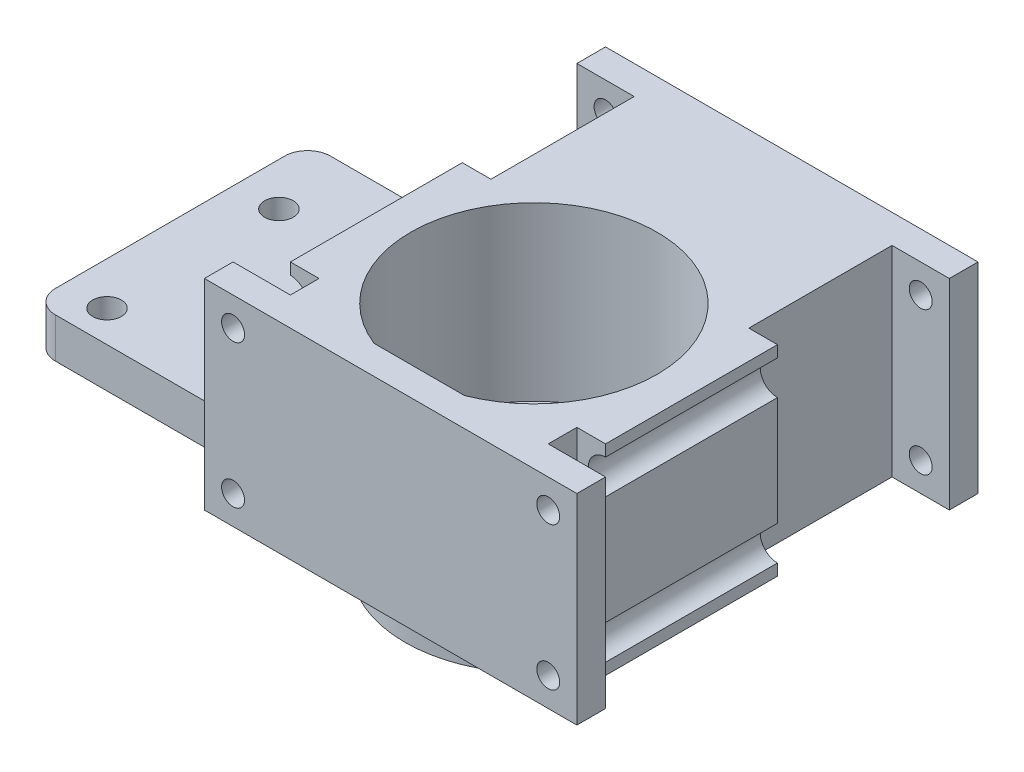
SolidWorks part; units mm, degrees
ref_plane "Front Plane" through (0, 0, 0) normal (0, 0, 1) x (1, 0, 0)
ref_plane "Top Plane" through (0, 0, 0) normal (0, 1, 0) x (1, 0, 0)
ref_plane "Right Plane" through (0, 0, 0) normal (1, 0, 0) x (0, 0, -1)
sketch "草图1" plane through (0, 0, 0) normal (0, 1, 0) x (1, 0, 0)
  line L0 (0, 0) -> (0, -10) construction
  line L1 (-22.5, -35) -> (22.5, -35)
  line L2 (-22.5, -35) -> (-22.5, 35)
  line L3 (-22.5, 35) -> (22.5, 35)
  line L4 (22.5, -35) -> (22.5, 35)
  line L5 (-22.5, -35) -> (22.5, 35) construction
  line L6 (-22.5, 35) -> (22.5, -35) construction
  circle A0 centre (0, 0) radius 21.5 construction
  circle A1 centre (0, -10) radius 21.5
  dimension "D1" = 43
  dimension "D2" = 70
  dimension "D4" = 43
  dimension "D3" = 45
  dimension "D5" = 10
extrude "凸台-拉伸1" add sketch "草图1" along normal blind 35
sketch "草图2" plane through (0, 0, 0) normal (0, -1, 0) x (1, 0, 0)
  circle A2 centre (0, 10) radius 21.5 construction
  circle A3 centre (0, 10) radius 21.5
extrude "凸台-拉伸2" add sketch "草图2" against normal blind 5
sketch "草图3" plane through (0, 0, 0) normal (0, -1, 0) x (1, 0, 0)
  line L0 (0, 27.5) -> (0, -7.5) construction
  line L1 (17.5, 10) -> (-17.5, 10) construction
  circle A0 centre (0, 10) radius 17.5 construction
  circle A1 centre (0, -7.5) radius 2
  circle A2 centre (-17.5, 10) radius 2
  circle A3 centre (0, 27.5) radius 2
  circle A4 centre (17.5, 10) radius 2
  circle A5 centre (0, 10) radius 13
  point P6 (0, 10)
  point P9 (0, 10)
  dimension "D1" = 35
  dimension "D2" = 4
  dimension "D3" = 26
  dimension "D4" = 10
extrude "切除-拉伸1" cut sketch "草图3" against normal blind 10
sketch "草图5" plane through (0, 0, -35) normal (0, 0, -1) x (-1, 0, 0)
  line L0 (-22.5, 35) -> (22.5, 35) construction
  line L1 (22.5, 0) -> (32.5, 0)
  line L2 (22.5, 0) -> (22.5, 35)
  line L3 (22.5, 35) -> (32.5, 35)
  line L4 (32.5, 0) -> (32.5, 35)
  line L5 (-22.5, 0) -> (-32.5, 0)
  line L6 (-22.5, 0) -> (-22.5, 35)
  line L7 (-22.5, 35) -> (-32.5, 35)
  line L8 (-32.5, 0) -> (-32.5, 35)
  dimension "D1" = 65
extrude "凸台-拉伸3" add sketch "草图5" against normal blind 5
sketch "草图6" plane through (0, 0, -30) normal (0, 0, 1) x (1, 0, 0)
  line L0 (0, 0) -> (0, 17.5) construction
  line L1 (-27.5, 5) -> (27.5, 5) construction
  line L2 (-27.5, 5) -> (-27.5, 30) construction
  line L3 (-27.5, 30) -> (27.5, 30) construction
  line L4 (27.5, 5) -> (27.5, 30) construction
  line L5 (-27.5, 5) -> (27.5, 30) construction
  line L6 (-27.5, 30) -> (27.5, 5) construction
  line L7 (32.5, 17.5) -> (0, 17.5) construction
  line L8 (32.5, 35) -> (32.5, 0) construction
  circle A0 centre (27.5, 30) radius 2
  circle A1 centre (27.5, 5) radius 2
  circle A2 centre (-27.5, 30) radius 2
  circle A3 centre (-27.5, 5) radius 2
  point P0 (0, 17.5)
  dimension "D3" = 4
  dimension "D1" = 55
  dimension "D2" = 25
extrude "切除-拉伸2" cut sketch "草图6" against normal blind 5
sketch "草图8" plane through (0, 0, 0) normal (0, -1, 0) x (1, 0, 0)
  circle A0 centre (0, 10) radius 22.5
  circle A1 centre (0, 10) radius 13 construction
  circle A2 centre (-17.5, 10) radius 2 construction
  circle A3 centre (0, -7.5) radius 2 construction
  circle A4 centre (0, 10) radius 13
  circle A5 centre (-17.5, 10) radius 2
  circle A6 centre (0, -7.5) radius 2
  circle A7 centre (17.5, 10) radius 2 construction
  circle A8 centre (0, 27.5) radius 2 construction
  circle A9 centre (17.5, 10) radius 2
  circle A10 centre (0, 27.5) radius 2
  dimension "D1" = 45
extrude "凸台-拉伸5" add sketch "草图8" along normal blind 5
sketch "草图9" plane through (0, -5, 0) normal (0, -1, 0) x (1, 0, 0)
  circle A0 centre (0, 27.5) radius 4
  circle A1 centre (-17.5, 10) radius 4
  circle A2 centre (17.5, 10) radius 4
  circle A3 centre (0, -7.5) radius 4
  dimension "D1" = 8
extrude "切除-拉伸3" cut sketch "草图9" against normal blind 5
sketch "草图10" plane through (0, -5, 0) normal (0, -1, 0) x (1, 0, 0)
  line L0 (0, 32.5) -> (-77, 32.5) construction
  line L1 (-77, 32.5) -> (-77, -12.5)
  line L2 (-77, -12.5) -> (0, -12.5)
  line L3 (-19.8997, 20.5) -> (-77, 20.5)
  arc A0 (22.5, 10) -> (-22.5, 10) centre (0, 10) ccw construction
  arc A1 (-22.5, 10) -> (22.5, 10) centre (0, 10) ccw construction
  circle A2 centre (0, 10) radius 22.5 construction
  arc A3 (-19.8997, 20.5) -> (0, -12.5) centre (0, 10) ccw
  circle M6 centre (0, 10) radius 22.5
  dimension "D1" = 12
  dimension "D2" = 77
extrude "凸台-拉伸6" add sketch "草图10" against normal blind 7 contours L3 L1 L2 M6
sketch "草图11" plane through (0, -5, 0) normal (0, -1, 0) x (1, 0, 0)
  line L1 (-77, -12.5) -> (-52, -12.5)
  line L2 (-77, -12.5) -> (-77, -27.5)
  line L3 (-77, -27.5) -> (-52, -27.5)
  line L4 (-52, -12.5) -> (-52, -27.5)
  dimension "D1" = 25
  dimension "D2" = 15
extrude "凸台-拉伸7" add sketch "草图11" against normal blind 7
fillet "圆角1" radius 4 4 edges at (-52, -1.5, -12.5) (-52, -1.5, -27.5) (-77, -1.5, -27.5) (-77, -1.5, 20.5)
sketch "草图12" plane through (0, -5, 0) normal (0, -1, 0) x (1, 0, 0)
  circle A0 centre (-69.5, -15) radius 2.5 construction
  circle A1 centre (-69.5, 15) radius 2.5 construction
  circle A2 centre (-69.5, -15) radius 2.5
  circle A3 centre (-69.5, 15) radius 2.5
extrude "切除-拉伸4" cut sketch "草图12" against normal blind 10
sketch "草图13" plane through (0, 0, 0) normal (0, 1, 0) x (1, 0, 0)
  line L0 (22.5, 5) -> (22.5, -25)
  line L1 (27.5, -25) -> (22.5, -25)
  line L2 (27.5, -25) -> (27.5, 5)
  line L3 (27.5, 5) -> (22.5, 5)
  line L4 (-27.5, -25) -> (-27.5, 5)
  line L5 (0, 5) -> (0, -25) construction
  line L6 (27.5, -10) -> (-27.5, -10) construction
  line L7 (22.5, -35) -> (22.5, 30) construction
  line L8 (-22.5, -25) -> (-22.5, 5)
  line L9 (-22.5, 30) -> (-22.5, -35) construction
  line L10 (-22.5, -20.5) -> (-22.5, 12.5) construction
  line L11 (-22.5, 5) -> (-27.5, 5)
  line L12 (-22.5, -25) -> (-27.5, -25)
  point P0 (0, -10)
  dimension "D1" = 55
  dimension "D2" = 30
extrude "凸台-拉伸8" add sketch "草图13" along normal blind 35
sketch "草图14" plane through (0, 0, 35) normal (0, 0, 1) x (1, 0, 0)
  line L0 (51.7919, 0) -> (-51.7919, 0) construction
  line L1 (-32.5, 35) -> (32.5, 35)
  line L2 (-32.5, 35) -> (-32.5, 0)
  line L3 (-32.5, 0) -> (32.5, 0)
  line L4 (32.5, 35) -> (32.5, 0)
  line L5 (32.5, 35) -> (32.5, 0) construction
extrude "凸台-拉伸9" add sketch "草图14" against normal blind 5
sketch "草图15" plane through (0, 0, 35) normal (0, 0, 1) x (1, 0, 0)
  line L0 (0, 35) -> (0, 0) construction
  line L1 (-32.5, 35) -> (32.5, 35) construction
  line L2 (-32.5, 17.5) -> (32.5, 17.5) construction
  line L3 (-32.5, 35) -> (-32.5, 0) construction
  line L4 (32.5, 0) -> (32.5, 35) construction
sketch "草图16" plane through (0, 0, 30) normal (0, 0, -1) x (-1, 0, 0)
  circle A0 centre (-27.5, 30) radius 2
  circle A1 centre (-27.5, 5) radius 2
  circle A2 centre (27.5, 30) radius 2
  circle A3 centre (27.5, 5) radius 2
extrude "切除-拉伸5" cut sketch "草图16" against normal blind 5
sketch "草图18" plane through (0, 0, -5) normal (0, 0, -1) x (-1, 0, 0)
  circle A0 centre (27.5, 30) radius 3
  circle A1 centre (27.5, 5) radius 3
  circle A2 centre (-27.5, 5) radius 3
  circle A3 centre (-27.5, 30) radius 3
  dimension "D1" = 6
  dimension "D2" = 6
  dimension "D3" = 6
  dimension "D4" = 6
extrude "切除-拉伸6" cut sketch "草图18" against normal blind 31
